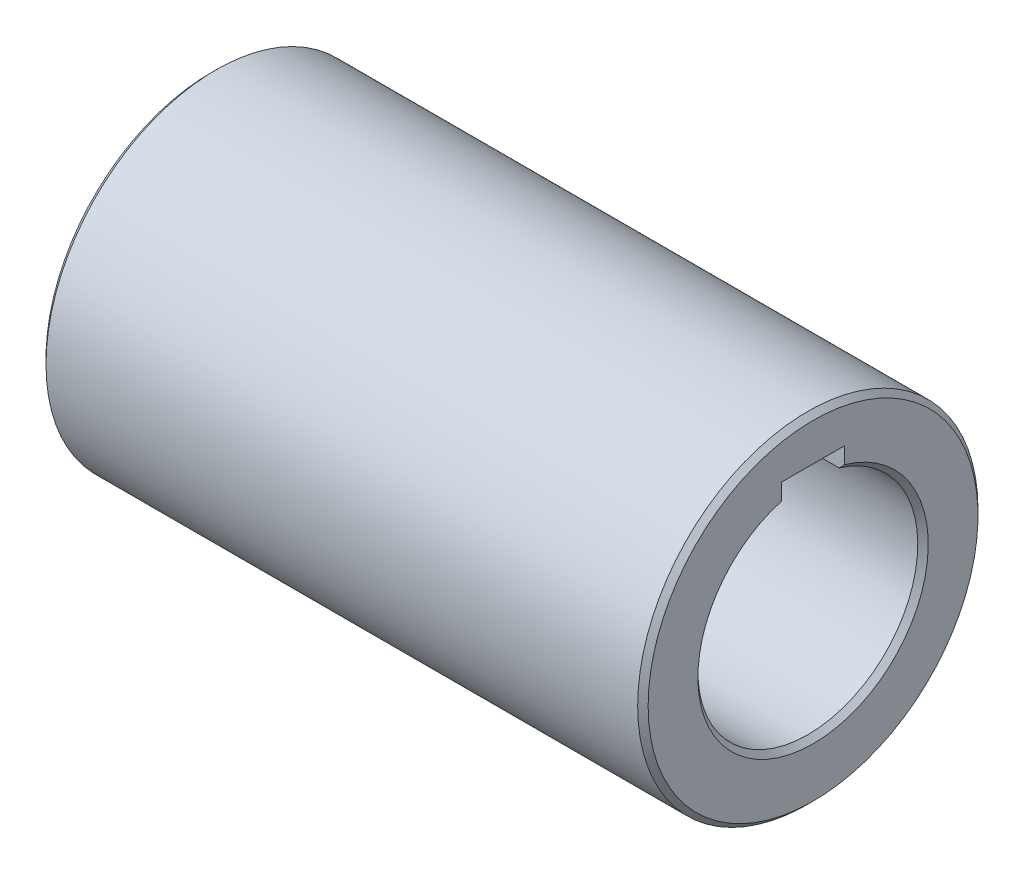
SolidWorks part; units mm, degrees
ref_plane "Front Plane" through (0, 0, 0) normal (0, 0, 1) x (1, 0, 0)
ref_plane "Top Plane" through (0, 0, 0) normal (0, 1, 0) x (1, 0, 0)
ref_plane "Right Plane" through (0, 0, 0) normal (1, 0, 0) x (0, 0, -1)
sketch "Sketch1" plane through (0, 0, 0) normal (0, 0, 1) x (1, 0, 0)
  line L0 (0, 0) -> (115.4321, 0) construction
  line L1 (0, 27.5) -> (0, 32.5)
  line L2 (0, 27.5) -> (63, 27.5)
  line L3 (63, 27.5) -> (63, 21)
  line L4 (63, 21) -> (115, 21)
  line L5 (115, 21) -> (115, 32.5)
  line L6 (115, 32.5) -> (0, 32.5)
  dimension "D1" = 55
  dimension "D2" = 63
  dimension "D3" = 42
  dimension "D4" = 52
  dimension "D5" = 65
revolve "Revolve1" add sketch "Sketch1" angle 360 about L0
chamfer "Chamfer1" distance 1 angle 45 4 edges at (0, 0, 32.5) (0, 0, 27.5) (115, 0, 21) (115, 0, 32.5)
sketch "Sketch2" plane through (115, 0, 0) normal (1, 0, 0) x (0, 0, -1)
  line L0 (0, 16) -> (0, 0) construction
  line L1 (6, 16) -> (-6, 16)
  line L2 (6, 16) -> (6, 24.3)
  line L3 (6, 24.3) -> (-6, 24.3)
  line L4 (-6, 16) -> (-6, 24.3)
  dimension "D2" = 24.3
  dimension "D1" = 12
  dimension "D3" = 8.3
  dimension "D4" = 16
extrude "Cut-Extrude1" cut sketch "Sketch2" against normal blind 100
